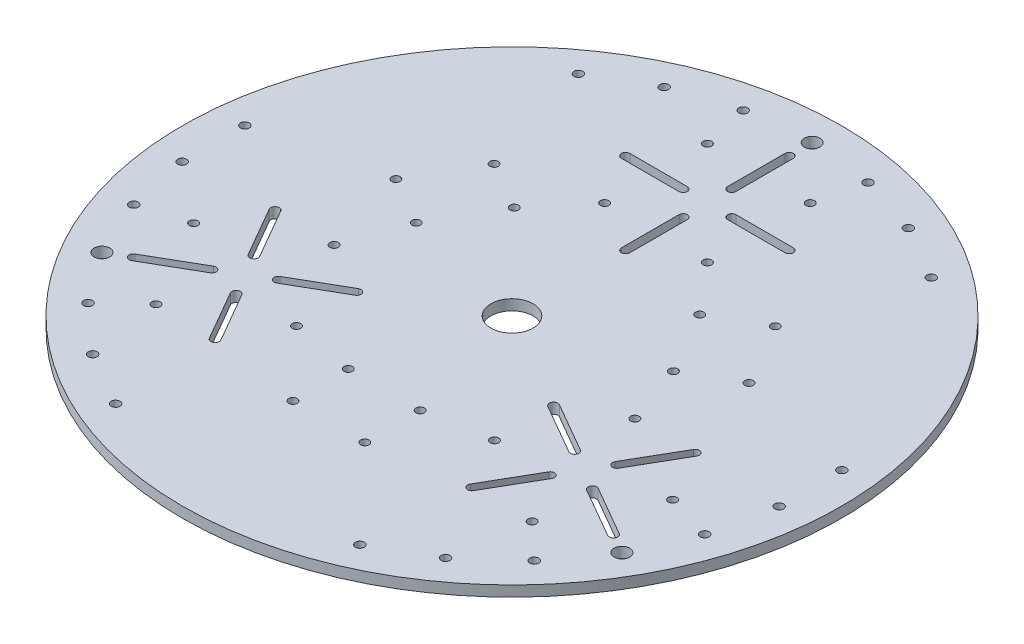
SolidWorks part; units mm, degrees
ref_plane "Front Plane" through (0, 0, 0) normal (0, 0, 1) x (1, 0, 0)
ref_plane "Top Plane" through (0, 0, 0) normal (0, 1, 0) x (1, 0, 0)
ref_plane "Right Plane" through (0, 0, 0) normal (1, 0, 0) x (0, 0, -1)
sketch "Sketch1" plane through (0, 0, 0) normal (0, 1, 0) x (1, 0, 0)
  line L0 (0, 0) -> (0, 125) construction
  line L1 (0, 0) -> (-17.3205, 10) construction
  line L2 (-89.4423, 25.0814) -> (-66.4423, 64.9186)
  line L3 (-68.2724, 71.7487) -> (-91.5024, 85.1605)
  line L4 (-96.2724, 23.2513) -> (-119.5024, 36.6631)
  line L5 (96.2724, 23.2513) -> (119.5024, 36.6631)
  line L6 (66.4423, 64.9186) -> (89.4423, 25.0814)
  line L7 (68.2724, 71.7487) -> (91.5024, 85.1605)
  line L8 (-28, -95) -> (-28, -121.8236)
  line L9 (23, -90) -> (-23, -90)
  line L10 (28, -95) -> (28, -121.8236)
  line L11 (-13.625, -48.465) -> (13.625, -48.465) construction
  line L12 (0, 0) -> (77.9423, 45) construction
  line L13 (0, 0) -> (-108.2532, -62.5) construction
  line L14 (-72.1832, -41.675) -> (-91.0626, -52.575) construction
  line L15 (-71.3832, -43.0606) -> (-90.2626, -53.9606)
  line L16 (-72.9832, -40.2894) -> (-91.8626, -51.1894)
  line L17 (-37.3257, -21.55) -> (-56.205, -32.45) construction
  line L18 (-36.5257, -22.9356) -> (-55.405, -33.8356)
  line L19 (-38.1257, -20.1644) -> (-57.005, -31.0644)
  line L20 (-72.1832, -41.675) -> (-56.205, -32.45) construction
  line L21 (-72.1832, -41.675) -> (-56.205, -32.45) construction
  line L22 (-68.8066, -29.0734) -> (-79.7066, -10.1941) construction
  line L23 (-70.1923, -29.8734) -> (-81.0923, -10.9941)
  line L24 (-67.421, -28.2734) -> (-78.321, -9.3941)
  line L25 (-56.205, -32.45) -> (-37.3257, -21.55) construction
  line L26 (-57.005, -31.0644) -> (-38.1257, -20.1644)
  line L27 (-55.405, -33.8356) -> (-36.5257, -22.9356)
  line L28 (-59.5816, -45.0516) -> (-48.6816, -63.9309) construction
  line L29 (-58.196, -44.2516) -> (-47.296, -63.1309)
  line L30 (-60.9673, -45.8516) -> (-50.0673, -64.7309)
  line L31 (0, 83.35) -> (0, 105.15) construction
  line L32 (-1.6, 83.35) -> (-1.6, 105.15)
  line L33 (1.6, 83.35) -> (1.6, 105.15)
  line L34 (0, 43.1) -> (0, 64.9) construction
  line L35 (-1.6, 43.1) -> (-1.6, 64.9)
  line L36 (1.6, 43.1) -> (1.6, 64.9)
  line L37 (9.225, 74.125) -> (31.025, 74.125) construction
  line L38 (9.225, 75.725) -> (31.025, 75.725)
  line L39 (9.225, 72.525) -> (31.025, 72.525)
  line L40 (-9.225, 74.125) -> (-31.025, 74.125) construction
  line L41 (-9.225, 72.525) -> (-31.025, 72.525)
  line L42 (-9.225, 75.725) -> (-31.025, 75.725)
  line L43 (72.1832, -41.675) -> (91.0626, -52.575) construction
  line L44 (72.9832, -40.2894) -> (91.8626, -51.1894)
  line L45 (71.3832, -43.0606) -> (90.2626, -53.9606)
  line L46 (37.3257, -21.55) -> (56.205, -32.45) construction
  line L47 (38.1257, -20.1644) -> (57.005, -31.0644)
  line L48 (36.5257, -22.9356) -> (55.405, -33.8356)
  line L49 (59.5816, -45.0516) -> (48.6816, -63.9309) construction
  line L50 (60.9673, -45.8516) -> (50.0673, -64.7309)
  line L51 (58.196, -44.2516) -> (47.296, -63.1309)
  line L52 (68.8066, -29.0734) -> (79.7066, -10.1941) construction
  line L53 (67.421, -28.2734) -> (78.321, -9.3941)
  line L54 (70.1923, -29.8734) -> (81.0923, -10.9941)
  line L55 (-49.8802, 55.605) -> (-73.0954, 15.395)
  line L56 (0, 0) -> (0, -90.0676) construction
  line L59 (13.625, -69.465) -> (-13.625, -69.465) construction
  line L60 (-13.625, -48.465) -> (-13.625, -69.465) construction
  line L61 (13.625, -48.465) -> (13.625, -69.465) construction
  line L62 (13.625, -71.065) -> (-13.625, -71.065) construction
  line L63 (8, -57) -> (-8, -57) construction
  line L64 (8, -57) -> (8, -73) construction
  line L65 (8, -73) -> (-8, -73) construction
  line L66 (-8, -57) -> (-8, -73) construction
  line L67 (8, -57) -> (-8, -73) construction
  line L68 (8, -73) -> (-8, -57) construction
  line L69 (8, -74.6) -> (-8, -74.6) construction
  circle A0 centre (0, 0) radius 8
  arc A1 (-119.5024, 36.6631) -> (-28, -121.8236) centre (0, 0) ccw
  circle A2 centre (0, 113.85) radius 2.95
  circle A3 centre (98.597, -56.925) radius 2.95
  circle A4 centre (-98.597, -56.925) radius 2.95
  circle A5 centre (0, 113.85) radius 1.675
  circle A6 centre (0, 0) radius 90 construction
  arc A7 (-89.4423, 25.0814) -> (-96.2724, 23.2513) centre (-93.7724, 27.5814) cw
  arc A8 (-66.4423, 64.9186) -> (-68.2724, 71.7487) centre (-70.7724, 67.4186) ccw
  arc A9 (89.4423, 25.0814) -> (96.2724, 23.2513) centre (93.7724, 27.5814) ccw
  arc A10 (66.4423, 64.9186) -> (68.2724, 71.7487) centre (70.7724, 67.4186) cw
  arc A11 (-23, -90) -> (-28, -95) centre (-23, -95) ccw
  arc A12 (23, -90) -> (28, -95) centre (23, -95) cw
  arc A13 (91.5024, 85.1605) -> (-91.5024, 85.1605) centre (0, 0) ccw
  arc A14 (28, -121.8236) -> (119.5024, 36.6631) centre (0, 0) ccw
  circle A15 centre (23.6707, 111.3621) radius 1.675
  circle A16 centre (46.307, 104.0072) radius 1.675
  circle A17 centre (66.9194, 92.1066) radius 1.675
  circle A21 centre (113.2263, 11.9006) radius 1.675
  circle A22 centre (113.2263, -11.9006) radius 1.675
  circle A23 centre (108.2778, -35.1816) radius 1.675
  circle A25 centre (84.607, -76.1805) radius 1.675
  circle A26 centre (66.9194, -92.1066) radius 1.675
  circle A27 centre (46.307, -104.0072) radius 1.675
  circle A31 centre (-46.307, -104.0072) radius 1.675
  circle A32 centre (-66.9194, -92.1066) radius 1.675
  circle A33 centre (-84.607, -76.1805) radius 1.675
  circle A35 centre (-108.2778, -35.1816) radius 1.675
  circle A36 centre (-113.2263, -11.9006) radius 1.675
  circle A37 centre (-113.2263, 11.9006) radius 1.675
  circle A41 centre (-66.9194, 92.1066) radius 1.675
  circle A42 centre (-46.307, 104.0072) radius 1.675
  circle A43 centre (-23.6707, 111.3621) radius 1.675
  circle A44 centre (-98.597, -56.925) radius 1.675 [skipped]
  circle A45 centre (98.597, -56.925) radius 1.675 [skipped]
  circle A46 centre (0, 0) radius 106.75 construction
  arc A47 (-71.3832, -43.0606) -> (-72.9832, -40.2894) centre (-72.1832, -41.675) ccw
  arc A48 (-91.8626, -51.1894) -> (-90.2626, -53.9606) centre (-91.0626, -52.575) ccw
  circle A49 centre (0, 0) radius 66.5 construction
  arc A50 (-36.5257, -22.9356) -> (-38.1257, -20.1644) centre (-37.3257, -21.55) ccw
  arc A51 (-57.005, -31.0644) -> (-55.405, -33.8356) centre (-56.205, -32.45) ccw
  circle A52 centre (-64.1941, -37.0625) radius 2 construction
  arc A53 (-70.1923, -29.8734) -> (-67.421, -28.2734) centre (-68.8066, -29.0734) ccw
  arc A54 (-78.321, -9.3941) -> (-81.0923, -10.9941) centre (-79.7066, -10.1941) ccw
  arc A55 (-57.005, -31.0644) -> (-55.405, -33.8356) centre (-56.205, -32.45) ccw
  arc A56 (-36.5257, -22.9356) -> (-38.1257, -20.1644) centre (-37.3257, -21.55) ccw
  arc A57 (-58.196, -44.2516) -> (-60.9673, -45.8516) centre (-59.5816, -45.0516) ccw
  arc A58 (-50.0673, -64.7309) -> (-47.296, -63.1309) centre (-48.6816, -63.9309) ccw
  arc A59 (-1.6, 83.35) -> (1.6, 83.35) centre (0, 83.35) ccw
  arc A60 (1.6, 105.15) -> (-1.6, 105.15) centre (0, 105.15) ccw
  arc A61 (-1.6, 43.1) -> (1.6, 43.1) centre (0, 43.1) ccw
  arc A62 (1.6, 64.9) -> (-1.6, 64.9) centre (0, 64.9) ccw
  arc A63 (9.225, 75.725) -> (9.225, 72.525) centre (9.225, 74.125) ccw
  arc A64 (31.025, 72.525) -> (31.025, 75.725) centre (31.025, 74.125) ccw
  arc A65 (-9.225, 72.525) -> (-9.225, 75.725) centre (-9.225, 74.125) ccw
  arc A66 (-31.025, 75.725) -> (-31.025, 72.525) centre (-31.025, 74.125) ccw
  arc A67 (72.9832, -40.2894) -> (71.3832, -43.0606) centre (72.1832, -41.675) ccw
  arc A68 (90.2626, -53.9606) -> (91.8626, -51.1894) centre (91.0626, -52.575) ccw
  arc A69 (38.1257, -20.1644) -> (36.5257, -22.9356) centre (37.3257, -21.55) ccw
  arc A70 (55.405, -33.8356) -> (57.005, -31.0644) centre (56.205, -32.45) ccw
  arc A71 (60.9673, -45.8516) -> (58.196, -44.2516) centre (59.5816, -45.0516) ccw
  arc A72 (47.296, -63.1309) -> (50.0673, -64.7309) centre (48.6816, -63.9309) ccw
  arc A73 (67.421, -28.2734) -> (70.1923, -29.8734) centre (68.8066, -29.0734) ccw
  arc A74 (81.0923, -10.9941) -> (78.321, -9.3941) centre (79.7066, -10.1941) ccw
  circle A75 centre (0, 0) radius 100.95 construction
  circle A76 centre (-61.4878, 35.5) radius 5 construction
  circle A77 centre (-90.8316, -29.925) radius 1.6
  circle A78 centre (-57.0566, -10.425) radius 1.6
  circle A79 centre (-37.5566, -44.2) radius 1.6
  circle A80 centre (-71.3316, -63.7) radius 1.6
  circle A81 centre (19.5, 93.625) radius 1.6
  circle A82 centre (19.5, 54.625) radius 1.6
  circle A83 centre (-19.5, 54.625) radius 1.6
  circle A84 centre (-19.5, 93.625) radius 1.6
  circle A85 centre (71.3316, -63.7) radius 1.6
  circle A86 centre (37.5566, -44.2) radius 1.6
  circle A87 centre (57.0566, -10.425) radius 1.6
  circle A88 centre (90.8316, -29.925) radius 1.6
  circle A89 centre (0, 0) radius 69.465 construction
  circle A90 centre (-13.625, -48.465) radius 1.6
  circle A91 centre (13.625, -48.465) radius 1.6
  circle A92 centre (13.625, -69.465) radius 1.6
  circle A93 centre (-13.625, -69.465) radius 1.6
  circle A94 centre (-35.1594, 36.0321) radius 1.6
  circle A95 centre (-48.7844, 12.4329) radius 1.6
  circle A96 centre (-66.971, 22.9329) radius 1.6
  circle A97 centre (-53.346, 46.5321) radius 1.6
  circle A98 centre (48.7844, 12.4329) radius 1.6
  circle A99 centre (35.1594, 36.0321) radius 1.6
  circle A100 centre (53.346, 46.5321) radius 1.6
  circle A101 centre (66.971, 22.9329) radius 1.6
  circle A102 centre (0, 0) radius 73 construction
  circle A115 centre (0, 0) radius 125
  circle A116 centre (-108.2778, 35.1816) radius 1.675 [skipped]
  circle A117 centre (-98.597, 56.925) radius 1.675 [skipped]
  circle A118 centre (-84.607, 76.1805) radius 1.675 [skipped]
  circle A119 centre (-23.6707, -111.3621) radius 1.675 [skipped]
  circle A120 centre (0, -113.85) radius 1.675 [skipped]
  circle A121 centre (23.6707, -111.3621) radius 1.675 [skipped]
  circle A122 centre (84.607, 76.1805) radius 1.675 [skipped]
  circle A123 centre (98.597, 56.925) radius 1.675 [skipped]
  circle A124 centre (108.2778, 35.1816) radius 1.675 [skipped]
  point P14 (0, 0)
  point P18 (-77.9423, 45)
  point P22 (-91.9423, 20.7513)
  point P25 (-63.9423, 69.2487)
  point P44 (0, 0)
  point P51 (0, 0)
  point P73 (0, 0)
  point P84 (-81.6229, -47.125)
  point P103 (0, 0)
  point P115 (-46.7654, -27)
  point P129 (-74.2566, -19.6337)
  point P136 (-46.7654, -27)
  point P143 (-54.1316, -54.4913)
  point P148 (-64.1941, -37.0625)
  point P150 (0, 94.25)
  point P157 (0, 54)
  point P164 (20.125, 74.125)
  point P171 (-20.125, 74.125)
  point P178 (81.6229, -47.125)
  point P185 (46.7654, -27)
  point P192 (54.1316, -54.4913)
  point P199 (74.2566, -19.6337)
  point P204 (0, 0)
  point P209 (-61.4878, 35.5)
  point P220 (-64.1941, -37.0625)
  point P237 (0, 0)
  point P245 (0, -65)
  point P264 (0, 0)
  point P295 (0, 0)
  dimension "D1" = 250
  dimension "D2" = 16
  dimension "D3" = 113.85
  dimension "D4" = 3
  dimension "D5" = 3.35
  dimension "D6" = 60
  dimension "D8" = 5
  dimension "D12" = 213.5
  dimension "D13" = 3.2
  dimension "D14" = 21.8
  dimension "D15" = 3.2
  dimension "D16" = 133
  dimension "D18" = 4
  dimension "D20" = 19
  dimension "D21" = 3.2
  dimension "D26" = 138.93
  dimension "D28" = 3.2
  dimension "D31" = 90
  dimension "D32" = 146
  dimension "D7" = 56
  dimension "D11" = 60
  dimension "D17" = 21.8
  dimension "D22" = 17.9
  dimension "D23" = 17.9
  dimension "D27" = 21
  dimension "D29" = 27.25
  dimension "D33" = 16
  dimension "D34" = 16
  dimension "D36" = 15.4
  dimension "D9" = 3
  dimension "D10" = 30
  dimension "D19" = 3
  dimension "D24" = 4
  dimension "D25" = 3
  dimension "D30" = 3
extrude "Boss-Extrude2" add sketch "Sketch1" along normal blind 4
